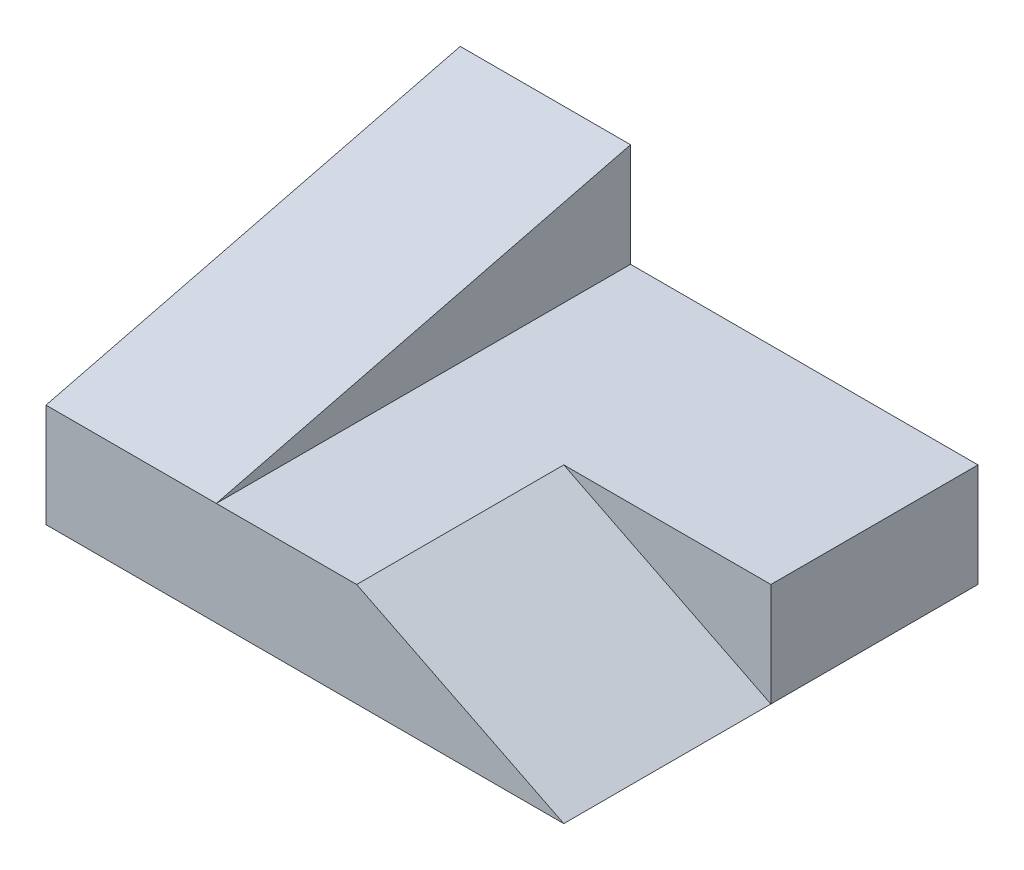
SolidWorks part; units mm, degrees
ref_plane "Front Plane" through (0, 0, 0) normal (0, 0, 1) x (1, 0, 0)
ref_plane "Top Plane" through (0, 0, 0) normal (0, 1, 0) x (1, 0, 0)
ref_plane "Right Plane" through (0, 0, 0) normal (1, 0, 0) x (0, 0, -1)
sketch "Sketch2" plane through (0, 0, 0) normal (0, 1, 0) x (1, 0, 0)
  line L2 (-25, -20) -> (25, -20)
  line L3 (-25, -20) -> (-25, 20)
  line L4 (-25, 20) -> (25, 20)
  line L5 (25, -20) -> (25, 20)
  line L6 (-25, -20) -> (25, 20) construction
  line L7 (-25, 20) -> (25, -20) construction
  point P1 (0, 0)
  dimension "D1" = 50
  dimension "D2" = 40
extrude "Boss-Extrude1" add sketch "Sketch2" along normal blind 10
sketch "Sketch3" plane through (0, 10, 0) normal (0, 1, 0) x (1, 0, 0)
  line L0 (-25, -20) -> (25, -20) construction
  line L1 (-25, 20) -> (-8.5533, 20)
  line L2 (-25, 20) -> (-25, -20)
  line L3 (-25, -20) -> (-8.5533, -20)
  line L4 (-8.5533, 20) -> (-8.5533, -20)
  dimension "D1" = 16.4467
extrude "Boss-Extrude3" add sketch "Sketch3" along normal blind 10
sketch "Sketch5" plane through (-8.5533, 0, 0) normal (1, 0, 0) x (0, 0, -1)
  line L0 (-20, 10) -> (20, 20)
  line L1 (20, 20) -> (-20, 20)
  line L2 (-20, 20) -> (-20, 10)
extrude "Cut-Extrude2" cut sketch "Sketch5" against normal blind 20
sketch "Sketch6" plane through (0, 0, 20) normal (0, 0, 1) x (1, 0, 0)
  line L0 (5, 10) -> (25, 0)
  line L1 (-8.5533, 10) -> (25, 10) construction
  line L2 (25, 0) -> (25, 10)
  line L3 (25, 10) -> (25, 0) construction
  line L4 (25, 10) -> (5, 10)
  dimension "D1" = 20
extrude "Cut-Extrude3" cut sketch "Sketch6" against normal blind 20
